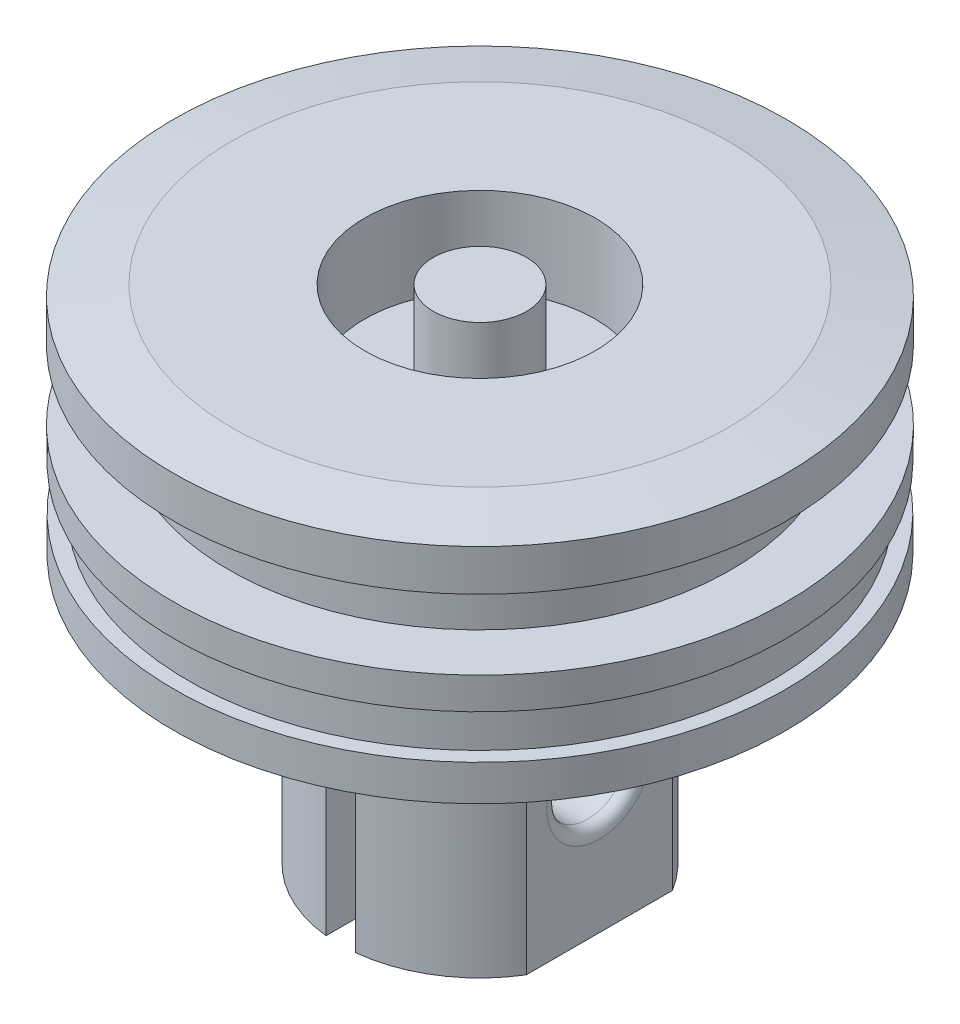
SolidWorks part; units mm, degrees
material "1060 Alloy"
ref_plane "Front Plane" through (0, 0, 0) normal (0, 0, 1) x (1, 0, 0)
ref_plane "Top Plane" through (0, 0, 0) normal (0, 1, 0) x (1, 0, 0)
ref_plane "Right Plane" through (0, 0, 0) normal (1, 0, 0) x (0, 0, -1)
sketch "Sketch1" plane through (0, 0, 0) normal (0, 0, 1) x (1, 0, 0)
  line L0 (0, 0) -> (13.3475, 0)
  line L1 (13.3475, 0) -> (13.3475, -2.248)
  line L2 (13.3475, -2.248) -> (10.9345, -2.248)
  line L3 (10.9345, -2.248) -> (10.9345, -5.296)
  line L4 (10.9345, -5.296) -> (13.3475, -5.296)
  line L5 (13.3475, -5.296) -> (13.3283, -6.6929)
  line L6 (13.3283, -6.6929) -> (12.6933, -6.6929)
  line L7 (12.6933, -6.6929) -> (12.6933, -8.5979)
  line L8 (12.6933, -8.5979) -> (13.3283, -8.5979)
  line L9 (13.3283, -8.5979) -> (13.3283, -10.16)
  line L10 (6.096, -10.16) -> (13.3283, -10.16)
  line L11 (0, -10.16) -> (0, 0)
  line L12 (0, 0) -> (0, 4.5049) construction
  line L13 (0, -10.16) -> (0, -21.844)
  line L14 (0, -21.844) -> (6.096, -21.844)
  line L15 (6.096, -21.844) -> (6.096, -10.16)
  dimension "D2" = 0.635
  dimension "D3" = 2.413
  dimension "D4" = 3.048
  dimension "D5" = 10.16
  dimension "D6" = 11.684
  dimension "D7" = 6.096
  dimension "D8" = 10.16
  dimension "D9" = 1.905
  dimension "D10" = 1.397
  dimension "D11" = 1.5621
  dimension "D12" = 0.635
  dimension "D13" = 13.3475
  dimension "D14" = 7.2323
revolve "Revolve1" add sketch "Sketch1" angle 360 about L12
chamfer "Chamfer1" distance 2.54 angle 10 1 edges at (0, 0, -13.3475)
ref_plane "Plane1" through (0, 0, 13.335) normal (0, 0, 1) x (1, 0, 0)
sketch "Sketch3" plane through (0, 0, 13.335) normal (0, 0, 1) x (1, 0, 0)
  line L0 (-0.635, -21.844) -> (0.635, -21.844)
  line L1 (6.096, -10.6764) -> (6.096, -21.844)
  line L2 (0.635, -21.844) -> (0.635, -10.16)
  line L3 (0.635, -10.16) -> (-0.635, -10.16)
  line L4 (-0.635, -10.16) -> (-0.635, -21.844)
  line L5 (10.8075, 0) -> (-10.8075, 0) construction
  line L6 (6.096, -21.844) -> (6.096, -10.16) construction
  line L7 (6.096, -10.6764) -> (5.1995, -10.6764)
  line L8 (5.1995, -10.6764) -> (5.1995, -21.844)
  line L9 (-6.096, -21.844) -> (6.096, -21.844) construction
  line L10 (6.096, -21.844) -> (5.1995, -21.844)
  line L11 (0, 0) -> (0, 7.3797) construction
  line L12 (-6.096, -21.844) -> (-5.1995, -21.844)
  line L13 (-6.096, -10.6764) -> (-6.096, -21.844)
  line L14 (-6.096, -10.6764) -> (-5.1995, -10.6764)
  line L15 (-5.1995, -10.6764) -> (-5.1995, -21.844)
  dimension "D1" = 1.27
  dimension "D2" = 11.684
  dimension "D3" = 10.16
  dimension "D4" = 0.635
  dimension "D5" = 0.5164
  dimension "D6" = 0.8965
extrude "Cut-Extrude2" cut sketch "Sketch3" against normal blind 25.4
ref_plane "Plane2" through (5.207, 0, 0) normal (1, 0, 0) x (0, 0, -1)
sketch "Sketch4" plane through (5.207, 0, 0) normal (1, 0, 0) x (0, 0, -1)
  line L0 (0, -16.0341) -> (0, -21.8761) construction
  circle A0 centre (0, -16.0341) radius 1.7833
  dimension "D1" = 3.5666
  dimension "D2" = 5.842
extrude "Cut-Extrude3" cut sketch "Sketch4" against normal through all contours A0
fillet "Fillet1" radius 0.508 1 edges at (5.1995, -16.0341, 1.7833)
sketch "Sketch5" plane through (0, 0, 0) normal (0, 1, 0) x (1, 0, 0)
  circle A0 centre (0, 0) radius 5.0165
  circle A1 centre (0, 0) radius 2.032
  dimension "D1" = 10.033
  dimension "D2" = 4.064
extrude "Cut-Extrude4" cut sketch "Sketch5" against normal blind 3.81
